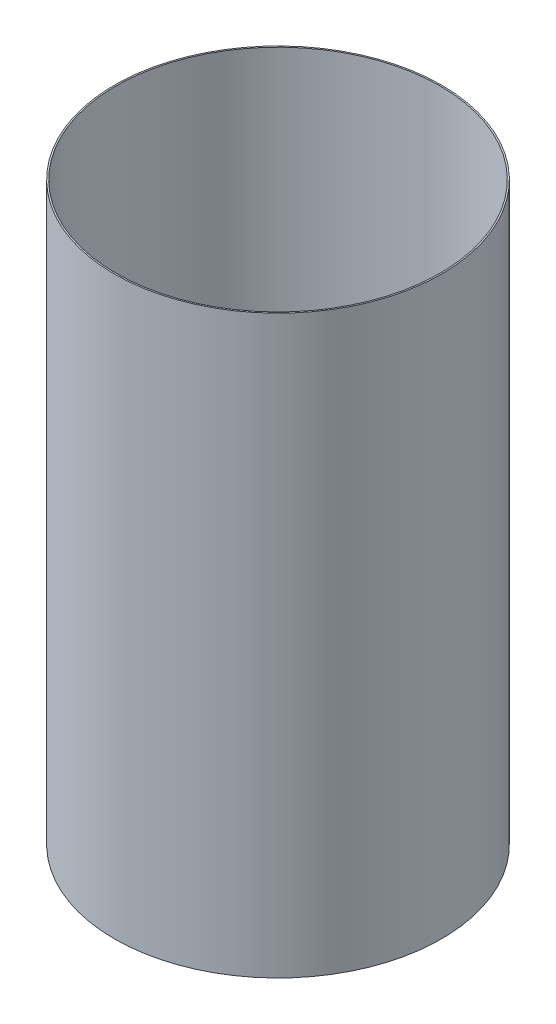
SolidWorks part; units mm, degrees
material "Простая углеродистая сталь"
ref_plane "Спереди" through (0, 0, 0) normal (0, 0, 1) x (1, 0, 0)
ref_plane "Сверху" through (0, 0, 0) normal (0, 1, 0) x (1, 0, 0)
ref_plane "Справа" through (0, 0, 0) normal (1, 0, 0) x (0, 0, -1)
sketch "Эскиз1" plane through (0, 0, 0) normal (0, 1, 0) x (1, 0, 0)
  circle A0 centre (0, 0) radius 222.5
extrude "Бобышка-Вытянуть1" add sketch "Эскиз1" along normal blind 790
shell "Оболочка1" thickness 2
